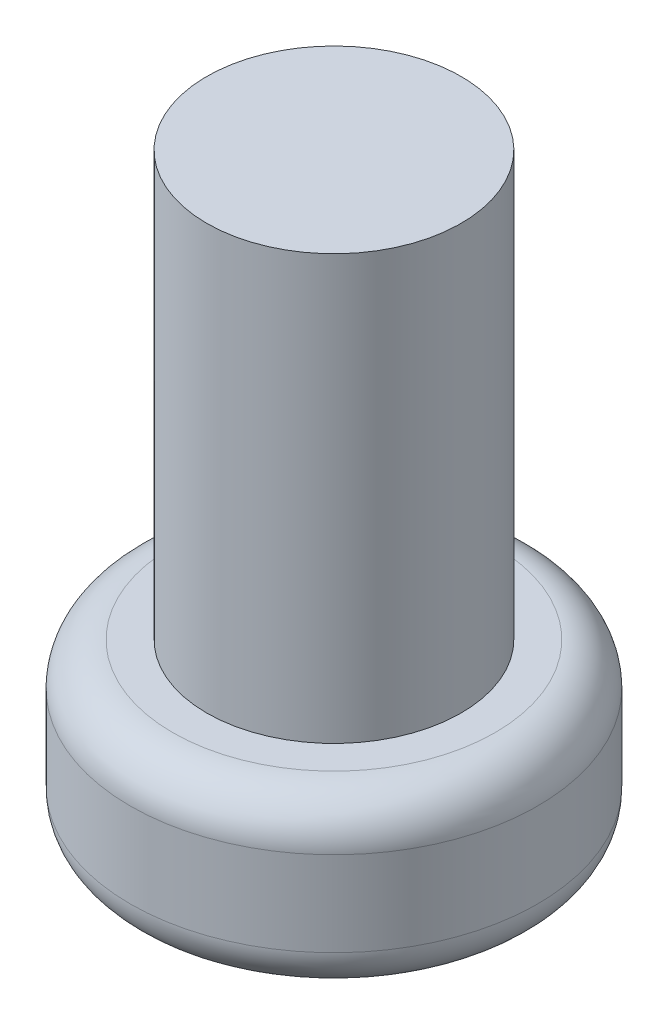
SolidWorks part; units mm, degrees
material "AISI 304"
ref_plane "Front Plane" through (0, 0, 0) normal (0, 0, 1) x (1, 0, 0)
ref_plane "Top Plane" through (0, 0, 0) normal (0, 1, 0) x (1, 0, 0)
ref_plane "Right Plane" through (0, 0, 0) normal (1, 0, 0) x (0, 0, -1)
sketch "Sketch1" plane through (0, 0, 0) normal (0, 1, 0) x (1, 0, 0)
  circle A0 centre (0, 0) radius 2.4
  dimension "D1" = 4.8
extrude "Boss-Extrude1" add sketch "Sketch1" along normal blind 2
sketch "Sketch2" plane through (0, 2, 0) normal (0, 1, 0) x (1, 0, 0)
  circle A0 centre (0, 0) radius 1.5
  dimension "D1" = 3
extrude "Boss-Extrude2" add sketch "Sketch2" along normal blind 5
fillet "Fillet1" radius 0.5 2 edges at (0, 0, 2.4) (0, 2, 2.4)
sketch "Sketch3" plane through (0, 0, 0) normal (0, -1, 0) x (1, 0, 0)
  line L0 (0.5, 0.5) -> (1.5, 0.5)
  line L1 (-0.5, -1.5) -> (0.5, -1.5)
  line L2 (-0.5, -1.5) -> (-0.5, -0.5)
  line L3 (-0.5, 1.5) -> (0.5, 1.5)
  line L4 (0.5, -1.5) -> (0.5, -0.5)
  line L5 (-0.5, -1.5) -> (0.5, 1.5) construction
  line L6 (-0.5, 1.5) -> (0.5, -1.5) construction
  line L7 (-1.5, 0.5) -> (-0.5, 0.5)
  line L8 (-1.5, 0.5) -> (-1.5, -0.5)
  line L9 (-1.5, -0.5) -> (-0.5, -0.5)
  line L10 (1.5, 0.5) -> (1.5, -0.5)
  line L11 (-1.5, 0.5) -> (1.5, -0.5) construction
  line L12 (-1.5, -0.5) -> (1.5, 0.5) construction
  line L13 (0.5, 0.5) -> (0.5, 1.5)
  line L14 (0.5, -0.5) -> (1.5, -0.5)
  line L15 (-0.5, 0.5) -> (-0.5, 1.5)
  point P0 (0, 0)
  point P6 (0, 0)
  dimension "D1" = 1
  dimension "D2" = 3
extrude "Cut-Extrude1" cut sketch "Sketch3" against normal blind 0.5
